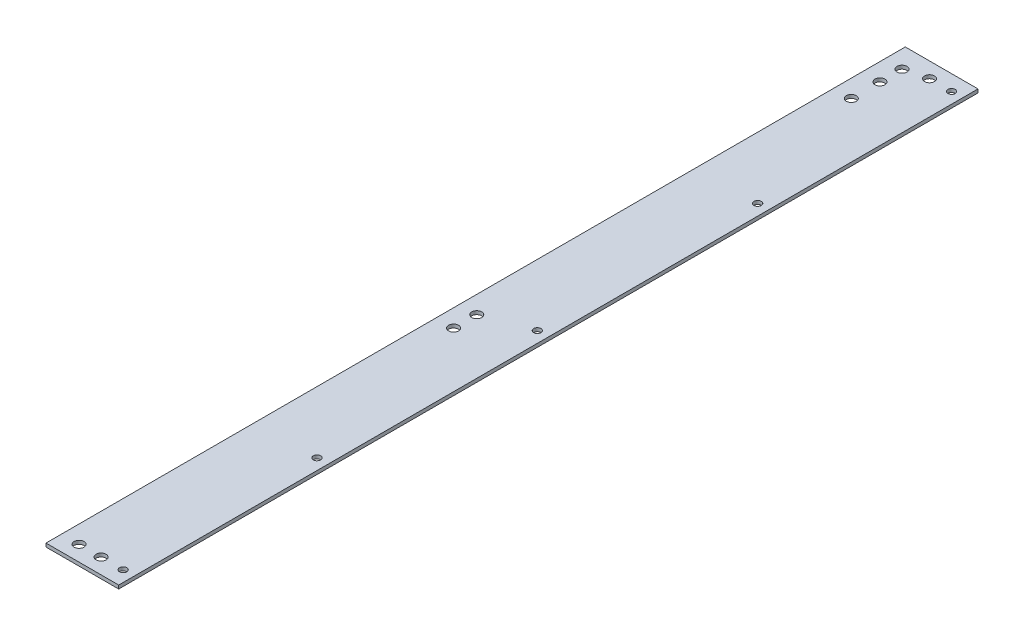
SolidWorks part; units mm, degrees
ref_plane "Front Plane" through (0, 0, 0) normal (0, 0, 1) x (1, 0, 0)
ref_plane "Top Plane" through (0, 0, 0) normal (0, 1, 0) x (1, 0, 0)
ref_plane "Right Plane" through (0, 0, 0) normal (1, 0, 0) x (0, 0, -1)
sketch "Sketch1" plane through (0, 0, 0) normal (0, 1, 0) x (1, 0, 0)
  line L1 (-16.5, -195) -> (16.5, -195)
  line L2 (-16.5, -195) -> (-16.5, 195)
  line L3 (-16.5, 195) -> (16.5, 195)
  line L4 (16.5, -195) -> (16.5, 195)
  line L5 (-16.5, -195) -> (16.5, 195) construction
  line L6 (-16.5, 195) -> (16.5, -195) construction
  point P0 (0, 0)
  dimension "D1" = 33
  dimension "D2" = 390
extrude "Boss-Extrude1" add sketch "Sketch1" along normal blind 1.5875
hole_wizard "M4 Clearance Hole1" positions "Sketch4" profile "Sketch5" hole size "M4" standard "ANSI Metric" end condition through all
sketch "Sketch4" plane through (0, 1.5875, 0) normal (0, 1, 0) x (1, 0, 0)
  line L4 (16.5, -195) -> (16.5, 195) construction
  line L5 (16.5, 195) -> (-16.5, 195) construction
  line L6 (-8.5, 185.5) -> (-8.5, 175.5)
  line L8 (-16.5, 195) -> (-16.5, -195) construction
  line L9 (-8.5, 162.5) -> (-8.5, -7.5)
  line L11 (-8.5, -18) -> (-8.5, -188)
  line L12 (-16.5, -195) -> (16.5, -195) construction
  line L13 (-0.8731, 0) -> (0.8731, 0) construction
  point P9 (1.5, 188)
  point P16 (-8.5, 185.5)
  point P17 (-8.5, 175.5)
  point P27 (-8.5, 162.5)
  point P28 (-8.5, -7.5)
  point P32 (-8.5, -18)
  point P33 (-8.5, -188)
  point P52 (1.5, -188)
  dimension "D1" = 15
  dimension "D2" = 7
  dimension "D3" = 10
  dimension "D4" = 9.5
  dimension "D5" = 8
  dimension "D6" = 170
  dimension "D7" = 13
  dimension "D8" = 10.5
  dimension "D9" = 170
  dimension "D10" = 7
sketch "Sketch5" plane through (1.5, 1.5875, -188) normal (1, 0, 0) x (0, 0, 1)
  line L0 (0, 0) -> (0, 1.5875)
  line L1 (0, 1.5875) -> (2.25, 1.5875)
  line L2 (2.25, 1.5875) -> (2.25, 0)
  line L5 (2.25, 0) -> (0, 0)
  line L11 (0, -6.35) -> (0, 107.95) construction
  dimension "Thru Hole Dia." = 4.5
  dimension "Thru Hole Depth" = 1.5875
hole_wizard "M4x0.7 Tapped Hole1" positions "Sketch6" profile "Sketch8" tap size "M4x0.7" standard "ANSI Metric" end condition through all
sketch "Sketch6" plane through (0, 1.5875, 0) normal (0, 1, 0) x (1, 0, 0)
  line L0 (16.5, -195) -> (16.5, 195) construction
  line L1 (16.5, 195) -> (-16.5, 195) construction
  line L2 (-0.8731, 0) -> (0.8731, 0) construction
  line L3 (11.5, 100) -> (11.5, -100)
  point P0 (11.5, 188)
  point P9 (11.5, -188)
  point P11 (11.5, 100)
  point P12 (11.5, -100)
  point P20 (11.5, 0)
  dimension "D1" = 5
  dimension "D2" = 7
  dimension "D3" = 200
  dimension "D4" = 5
sketch "Sketch8" plane through (11.5, 1.5875, -188) normal (1, 0, 0) x (0, 0, 1)
  line L0 (0, 0) -> (0, 1.5875)
  line L1 (0, 1.5875) -> (1.65, 1.5875)
  line L2 (1.65, 1.5875) -> (1.65, 0)
  line L5 (1.65, 0) -> (0, 0)
  line L11 (0, -6.35) -> (0, 107.95) construction
  dimension "Thru Tap Drill Dia." = 3.3
  dimension "Thru Tap Drill Depth" = 1.5875
cosmetic thread "Hole Thread1" parameters "D2"=4
cosmetic thread "Hole Thread2" parameters "D2"=4
cosmetic thread "Hole Thread3" parameters "D2"=4
cosmetic thread "Hole Thread4" parameters "D2"=4
cosmetic thread "Hole Thread5" parameters "D2"=4
